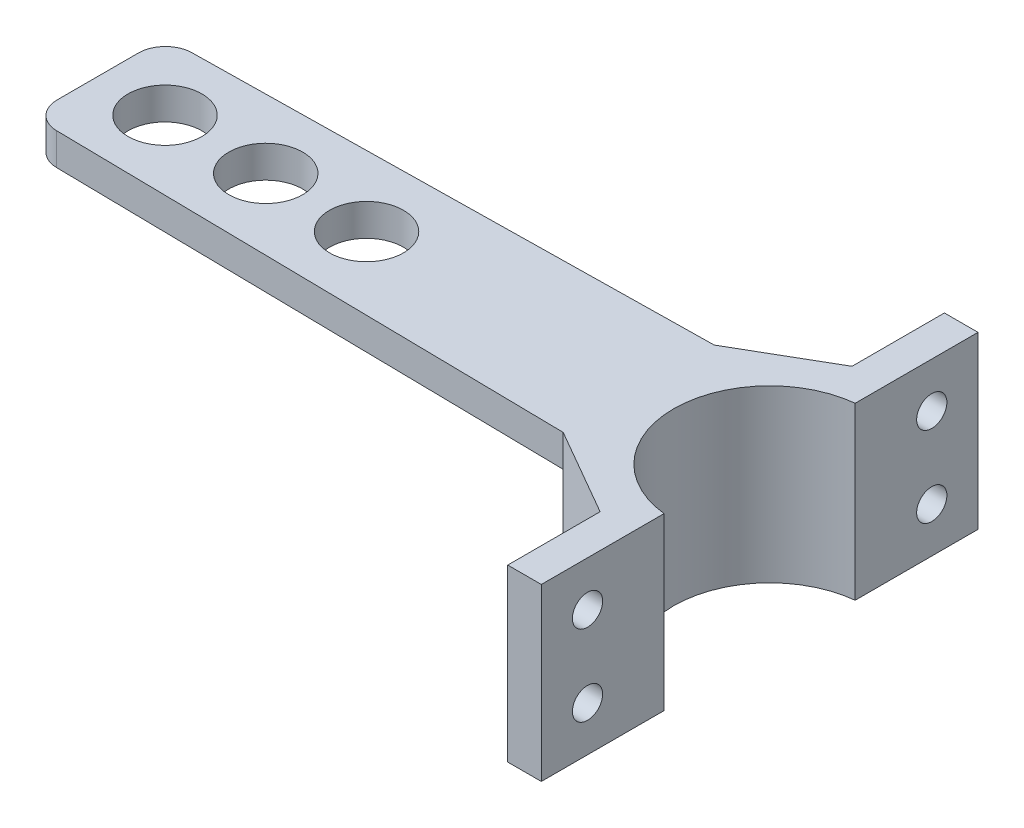
SolidWorks part; units mm, degrees
ref_plane "Front Plane" through (0, 0, 0) normal (0, 0, 1) x (1, 0, 0)
ref_plane "Top Plane" through (0, 0, 0) normal (0, 1, 0) x (1, 0, 0)
ref_plane "Right Plane" through (0, 0, 0) normal (1, 0, 0) x (0, 0, -1)
sketch "Sketch1" plane through (0, 0, 0) normal (0, 1, 0) x (1, 0, 0)
  line L0 (0, -14.3) -> (0, 14.3)
  line L1 (-1.5, 14.2211) -> (-1.5, 21.6429)
  line L2 (-0.0183, 22.5) -> (-19.4947, 11.2342)
  line L3 (-19.4947, 11.2342) -> (-19.4764, -11.2658)
  line L4 (-19.4764, -11.2658) -> (0.0183, -22.5)
  line L5 (0.0183, -22.5) -> (19.4947, -11.2342)
  line L6 (19.4947, -11.2342) -> (19.4764, 11.2658)
  line L7 (19.4764, 11.2658) -> (-0.0183, 22.5)
  line L8 (-1.5, -14.2211) -> (-1.5, -21.6251)
  line L9 (-1.5, 21.6429) -> (-1.5, 32.5035)
  line L10 (-1.5, 32.5035) -> (-6.5, 32.5035)
  line L11 (-6.5, 32.5035) -> (-6.5, 18.7507)
  line L12 (-1.5, -21.6251) -> (-1.5, -32.4965)
  line L13 (-1.5, -32.4965) -> (-6.5, -32.4965)
  line L14 (-6.5, -32.4965) -> (-6.5, -18.7437)
  circle A0 centre (0, 0) radius 14.3
  circle A2 centre (0, 0) radius 19.4856 construction
  point P6 (0, 0)
  dimension "D1" = 28.6
  dimension "D2" = 45
  dimension "D3" = 1.5
  dimension "D4" = 5
  dimension "D5" = 65
extrude "Boss-Extrude1" add sketch "Sketch1" along normal blind 25.4 contours L10 L11 L2 L9 | A0 L1 L2 L3 L4 L8 | L14 L13 L12 L4
sketch "Sketch2" plane through (-6.5, 0, 0) normal (-1, 0, 0) x (0, 0, 1)
  line L0 (25.6201, 25.4) -> (25.6201, 18.7) construction
  line L3 (32.4965, 25.4) -> (18.7437, 25.4) construction
  line L4 (25.6201, 18.7) -> (25.6201, 6.7) construction
  line L5 (25.6201, 6.7) -> (25.6201, 0) construction
  line L6 (32.4965, 0) -> (18.7437, 0) construction
  circle A0 centre (25.6201, 18.7) radius 2.25
  circle A1 centre (25.6201, 6.7) radius 2.25
  dimension "D1" = 4.5
  dimension "D2" = 12
extrude "Cut-Extrude1" cut sketch "Sketch2" against normal through all
mirror "Mirror1" about plane through (0, 0, 0) normal (0, 0, 1) of "Cut-Extrude1"
sketch "Sketch3" plane through (0, 25.4, 0) normal (0, 1, 0) x (1, 0, 0)
  line L0 (-19.4947, 11.2342) -> (-100, 9.9842)
  line L1 (-100, 9.9842) -> (-100, -10.0158)
  line L2 (-100, -10.0158) -> (-19.4764, -11.2658)
  line L3 (-100, -0.0158) -> (-19.4856, -0.0158) construction
  line L4 (-19.4947, 11.2342) -> (-19.4764, -11.2658) construction
  line L5 (-90, -0.0158) -> (-75, -0.0158) construction
  line L6 (-75, -0.0158) -> (-60, -0.0158) construction
  circle A0 centre (-90, -0.0158) radius 5.5
  circle A1 centre (-75, -0.0158) radius 5.5
  circle A2 centre (-60, -0.0158) radius 5.5
  line M9 (-19.4947, 11.2342) -> (-19.4764, -11.2658)
  dimension "D3" = 11
  dimension "D1" = 100
  dimension "D2" = 20
  dimension "D4" = 15
  dimension "D5" = 10
extrude "Boss-Extrude2" add sketch "Sketch3" against normal blind 4.7625 contours L1 L2 L0 A2 A1 A0 M9
fillet "Fillet1" radius 4 2 edges at (-100, 23.0187, 10.0158) (-100, 23.0187, -9.9842)
equation "\"forkdia\"=28.6"
equation "\"D1@Sketch1\"=\"forkdia\""
